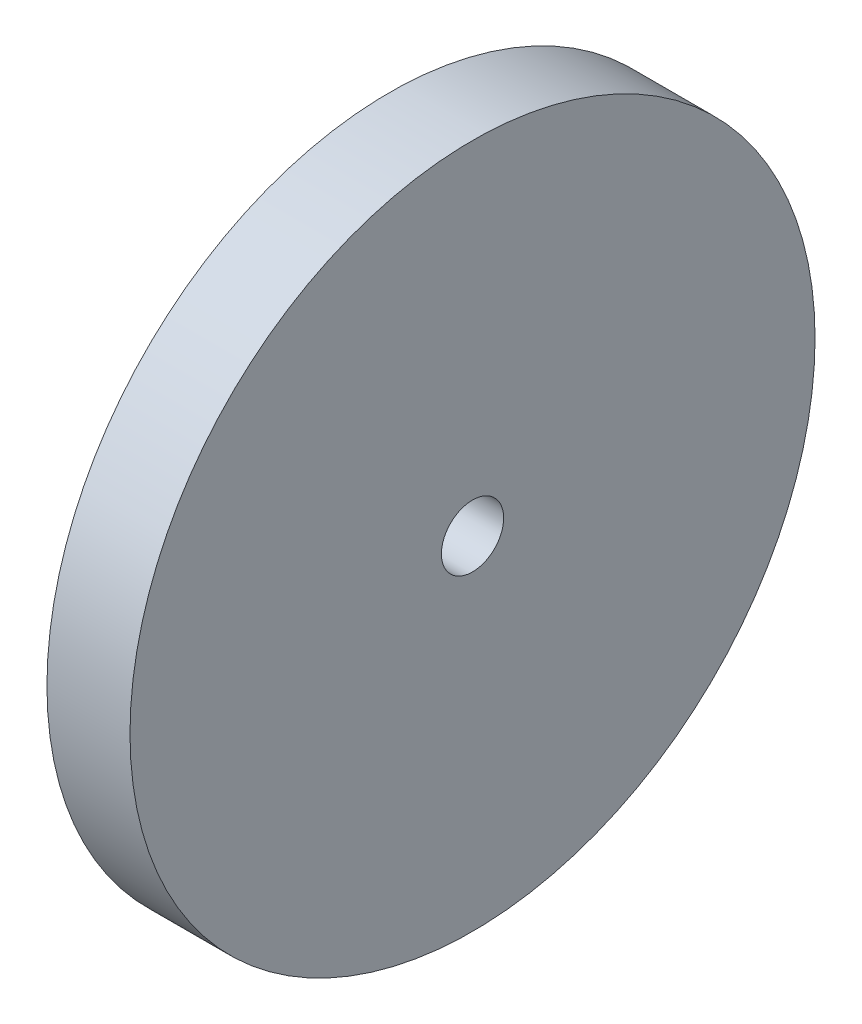
SolidWorks part; units mm, degrees
ref_plane "Plano frontal" through (0, 0, 0) normal (0, 0, 1) x (1, 0, 0)
ref_plane "Plano superior" through (0, 0, 0) normal (0, 1, 0) x (1, 0, 0)
ref_plane "Plano direito" through (0, 0, 0) normal (1, 0, 0) x (0, 0, -1)
sketch "Esboço1" plane through (0, 0, 0) normal (1, 0, 0) x (0, 0, -1)
  circle A0 centre (0, 0) radius 16.5
  circle A1 centre (0, 0) radius 1.5
extrude "Ressalto-extrusão1" add sketch "Esboço1" along normal blind 4
